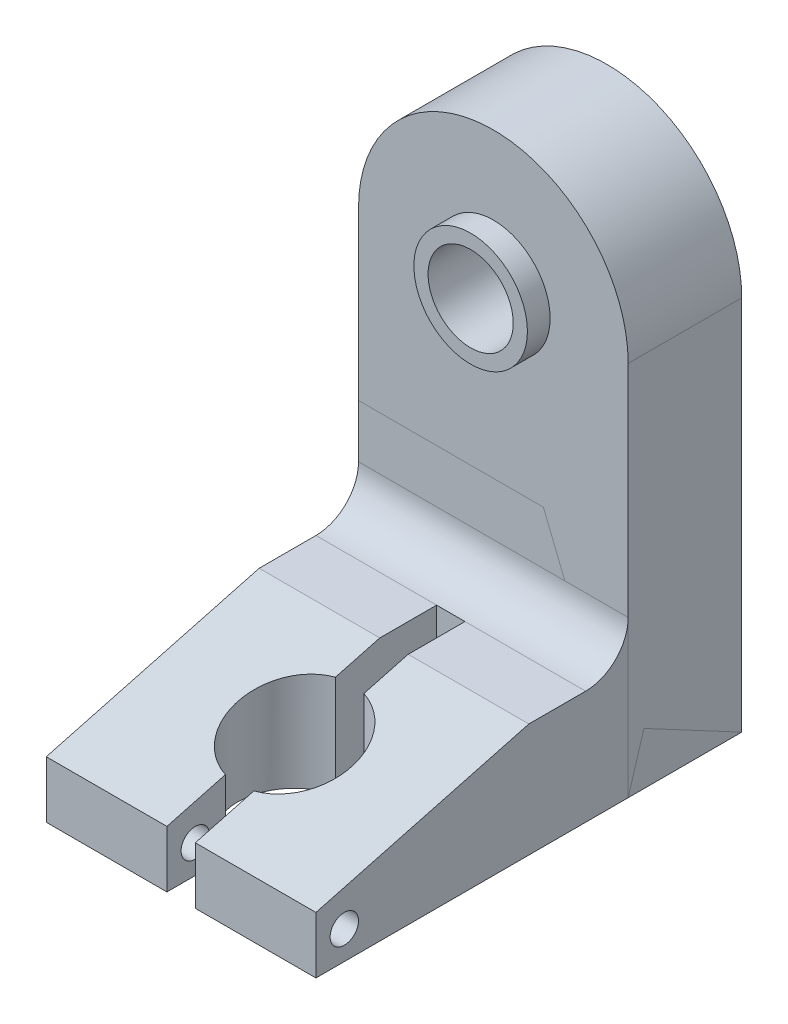
SolidWorks part; units mm, degrees
ref_plane "Alzado" through (0, 0, 0) normal (0, 0, 1) x (1, 0, 0)
ref_plane "Planta" through (0, 0, 0) normal (0, 1, 0) x (1, 0, 0)
ref_plane "Vista lateral" through (0, 0, 0) normal (1, 0, 0) x (0, 0, -1)
sketch "Croquis1" plane through (0, 0, 0) normal (0, 0, 1) x (1, 0, 0)
  line L2 (-47.5, 66.25) -> (-47.5, -66.25)
  line L3 (-47.5, -66.25) -> (47.5, -66.25)
  line L4 (47.5, 66.25) -> (47.5, -66.25)
  line L5 (-15.2451, 21.2629) -> (47.5, -66.25) construction
  line L6 (-47.5, -66.25) -> (0, 0) construction
  arc A0 (47.5, 66.25) -> (-47.5, 66.25) centre (0, 66.25) ccw
  circle A1 centre (0, 66.25) radius 15
  point P0 (0, 0)
  dimension "D3" = 30
  dimension "D1" = 132.5
  dimension "D2" = 95
extrude "Saliente-Extruir1" add sketch "Croquis1" along normal blind 40
sketch "Croquis2" plane through (-47.5, 0, 0) normal (-1, 0, 0) x (0, 0, 1)
  line L0 (40, -26.25) -> (75, -26.25)
  line L1 (40, -66.25) -> (150, -66.25)
  line L4 (150, -66.25) -> (150, -46.25)
  line L5 (75, -26.25) -> (150, -46.25)
  line L6 (40, -26.25) -> (40, 7.4455)
  line L7 (40, 66.25) -> (40, -66.25) construction
  line L8 (40, 7.4455) -> (0, 7.4455)
  line L9 (0, 66.25) -> (0, -66.25) construction
  line L10 (0, 7.4455) -> (0, -66.25)
  line L11 (0, -66.25) -> (40, -66.25)
  dimension "D1" = 20
  dimension "D2" = 40
  dimension "D3" = 35
  dimension "D4" = 150
extrude "Saliente-Extruir2" add sketch "Croquis2" against normal blind 95 separate body
fillet "Redondeo1" radius 15 1 edges at (0, -26.25, 40)
sketch "Croquis3" plane through (0, -26.25, 0) normal (0, 1, 0) x (1, 0, 0)
  line L0 (0, -55) -> (5, -55)
  line L1 (47.5, -55) -> (-47.5, -55) construction
  line L2 (5, -55) -> (5, -90.6351)
  line L3 (5, -129.3649) -> (5, -150)
  line L4 (47.5, -150) -> (-47.5, -150) construction
  line L5 (5, -150) -> (-5, -150)
  line L6 (-5, -150) -> (-5, -129.3649)
  line L7 (-5, -55) -> (0, -55)
  line L8 (0, -150) -> (0, -110) construction
  line L9 (-5, -90.6351) -> (-5, -55)
  arc A0 (-5, -90.6351) -> (-5, -129.3649) centre (0, -110) ccw
  arc A1 (5, -129.3649) -> (5, -90.6351) centre (0, -110) ccw
  dimension "D4" = 40
  dimension "D1" = 10
  dimension "D2" = 5
  dimension "D3" = 40
extrude "Cortar-Extruir1" cut sketch "Croquis3" against normal blind 95
sketch "Croquis4" plane through (47.5, 0, 0) normal (1, 0, 0) x (0, 0, -1)
  line L0 (-150, -56.25) -> (-140, -56.25) construction
  line L1 (-150, -66.25) -> (-150, -46.25) construction
  line L2 (-140, -56.25) -> (-140, -66.25) construction
  circle A0 centre (-140, -56.25) radius 5
  dimension "D3" = 10
  dimension "D1" = 10
  dimension "D2" = 10
extrude "Cortar-Extruir2" cut sketch "Croquis4" against normal blind 95
sketch "Croquis5" plane through (0, 0, 40) normal (0, 0, 1) x (1, 0, 0)
  circle A0 centre (0, 66.25) radius 15
  circle A1 centre (0, 66.25) radius 20
  dimension "D1" = 30
  dimension "D2" = 40
extrude "Saliente-Extruir3" add sketch "Croquis5" along normal blind 8
